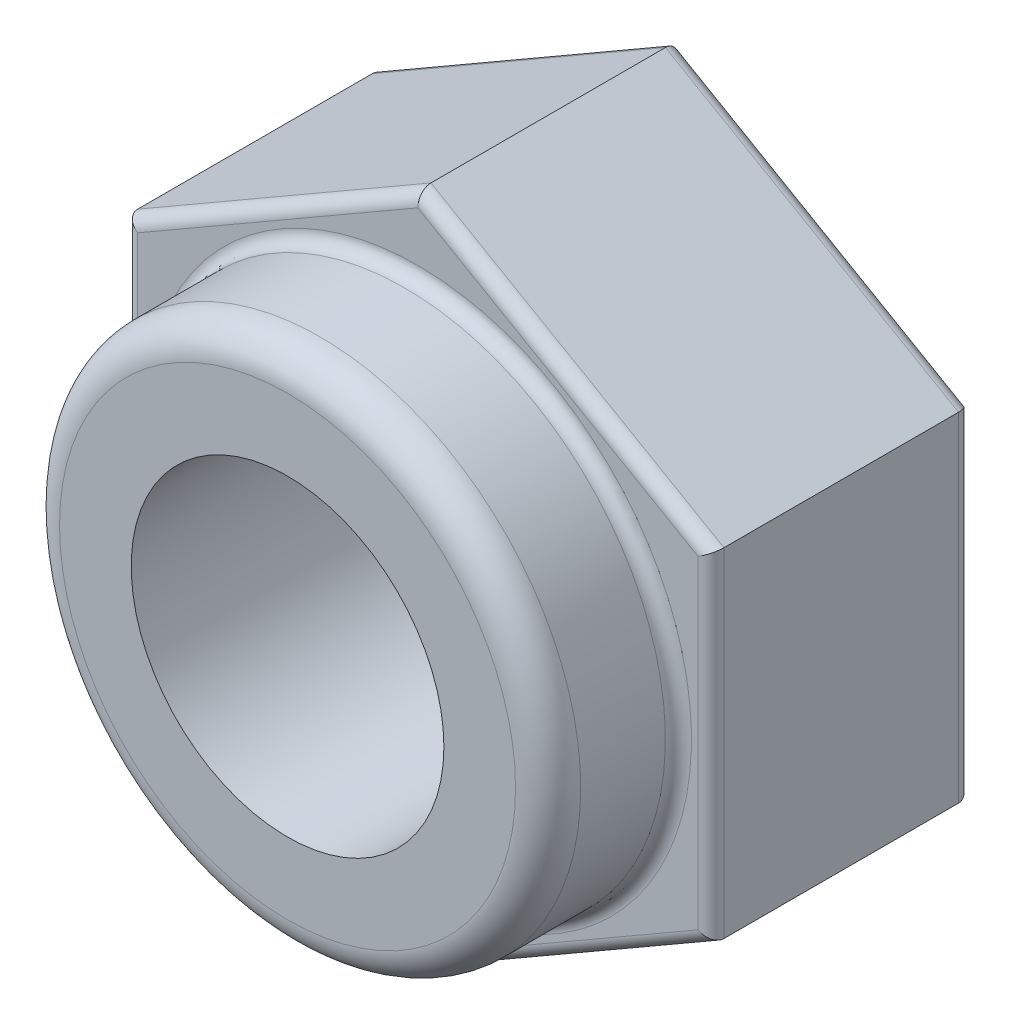
SolidWorks part; units mm, degrees
material "AISI 316 Annealed Stainless Steel Bar (SS)"
ref_plane "Front Plane" through (0, 0, 0) normal (0, 0, 1) x (1, 0, 0)
ref_plane "Top Plane" through (0, 0, 0) normal (0, 1, 0) x (1, 0, 0)
ref_plane "Right Plane" through (0, 0, 0) normal (1, 0, 0) x (0, 0, -1)
sketch "Sketch1" plane through (0, 0, 0) normal (0, 0, 1) x (1, 0, 0)
  line L0 (-5.715, 3.2996) -> (-5.715, -3.2996)
  line L1 (5.715, 3.2996) -> (5.715, -3.2996)
  line L2 (-5.715, 3.2996) -> (0, 6.5991)
  line L3 (0, 6.5991) -> (5.715, 3.2996)
  line L4 (-5.715, -3.2996) -> (0, -6.5991)
  line L5 (0, -6.5991) -> (5.715, -3.2996)
  point P4 (5.715, 0)
  point P7 (-5.715, 0)
  dimension "D1" = 11.43
  dimension "D2" = 11.43
extrude "Boss-Extrude1" add sketch "Sketch1" along normal blind 5.08
sketch "Sketch3" plane through (0, 0, 5.08) normal (0, 0, 1) x (1, 0, 0)
  circle A0 centre (0, 0) radius 5.08
  dimension "D1" = 10.16
extrude "Boss-Extrude3" add sketch "Sketch3" along normal blind 2.54
fillet "Fillet1" radius 0.635 1 edges at (5.08, 0, 7.62)
sketch "Sketch4" plane through (0, 0, 7.62) normal (0, 0, 1) x (1, 0, 0)
  circle A0 centre (0, 0) radius 3.048
  dimension "D1" = 6.096
extrude "Cut-Extrude1" cut sketch "Sketch4" against normal through all
fillet "Fillet2" radius 0.254 7 edges at (-5.715, 0, 0) (-2.8575, -4.9493, 0) (2.8575, -4.9493, 0) (5.715, 0, 0) (2.8575, 4.9493, 0) (-2.8575, 4.9493, 0) (3.048, 0, 0)
fillet "Fillet3" radius 0.254 7 edges at (2.8575, 4.9493, 5.08) (5.715, 0, 5.08) (2.8575, -4.9493, 5.08) (-2.8575, -4.9493, 5.08) (-5.715, 0, 5.08) (-2.8575, 4.9493, 5.08) (5.08, 0, 5.08)
